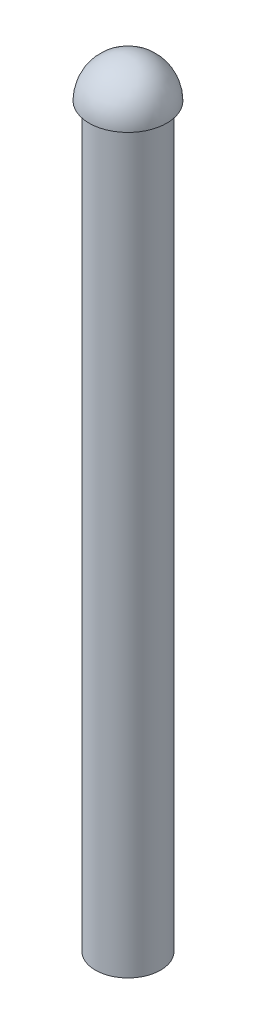
SolidWorks part; units mm, degrees
ref_plane "前视基准面" through (0, 0, 0) normal (0, 0, 1) x (1, 0, 0)
ref_plane "上视基准面" through (0, 0, 0) normal (0, 1, 0) x (1, 0, 0)
ref_plane "右视基准面" through (0, 0, 0) normal (1, 0, 0) x (0, 0, -1)
other "Configuration Table"
sketch "草图1" plane through (0, 0, 0) normal (0, 1, 0) x (1, 0, 0)
  line L0 (0, 7.75) -> (0, -7.75)
  arc A0 (0, -7.75) -> (0, 7.75) centre (0, 0) ccw
  dimension "D1" = 15.5
revolve "旋转1" add sketch "草图1" angle 180 about L0
sketch "草图6" plane through (0, 0, 0) normal (1, 0, 0) x (0, 0, -1)
  line L1 (0, 0) -> (6.5, 0)
  line L2 (0, 0) -> (0, -146.9)
  line L3 (0, -146.9) -> (6.5, -146.9)
  line L4 (6.5, 0) -> (6.5, -146.9)
  dimension "D1" = 6.5
  dimension "D2" = 146.9
revolve "旋转2" add sketch "草图6" angle 360 about L2
hole_wizard "M8 螺纹孔1" positions "3D草图1" profile "草图8" tap size "M8" standard "GB"
sketch3d "3D草图1"
  line L0 (0, 0, -7.75) -> (0, 0, 7.75) construction
  circle A0 centre (0, -146.9, 0) radius 6.5 construction
  point P0 (0, 0, 1.5941)
  point P4 (0, -146.9, 0)
  point P7 (0, -140.4, 0)
  dimension "D1" = 0
sketch "草图8" plane through (0, -146.9, 0) normal (1, 0, 0) x (0, 0, -1)
  line L0 (0, 0) -> (0, 21.7929)
  line L1 (0, 21.7929) -> (3.4, 19.75)
  line L2 (3.4, 19.75) -> (3.4, 0.625)
  line L3 (3.4, 0.625) -> (4.025, 0)
  line L5 (4.025, 0) -> (0, 0)
  line L6 (-3.4, 0.625) -> (-4.025, 0) construction
  line L10 (0, 21.7929) -> (-3.4, 19.75) construction
  line L11 (0, -6.35) -> (0, 107.95) construction
  point P5 (0, 0)
  dimension "螺纹孔钻头直径" = 6.8
  dimension "螺纹孔钻头深度" = 19.75
  dimension "近端锥形沉头孔直径" = 8.05
  dimension "近端锥形沉头孔角度" = 90
  dimension "导头角度" = 118
cosmetic thread "孔螺纹线8" parameters "D1"=16, "D2"=8
